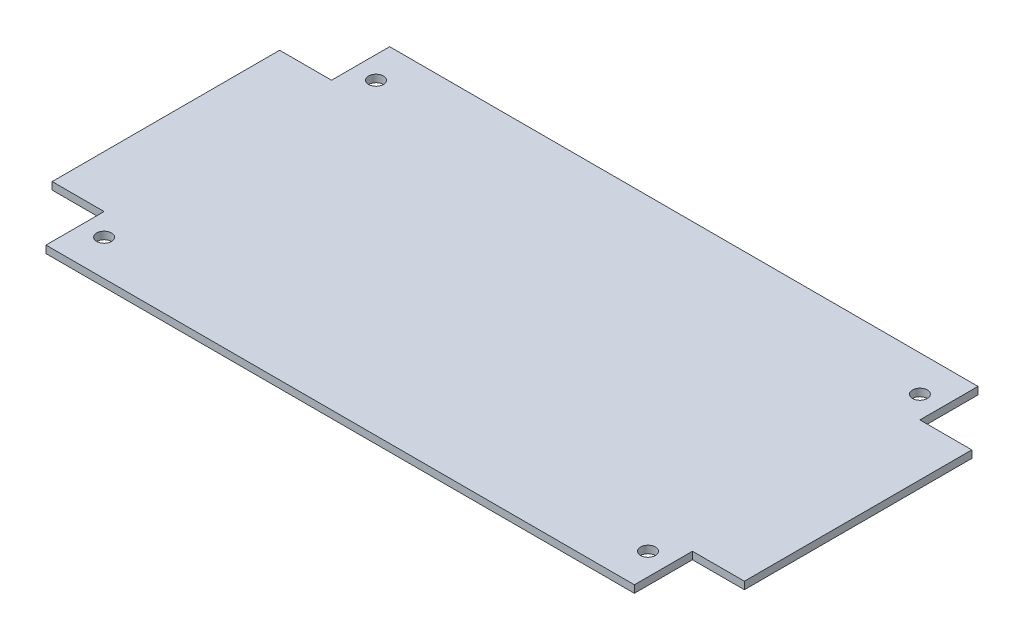
SolidWorks part; units mm, degrees
ref_plane "Спереди" through (0, 0, 0) normal (0, 0, 1) x (1, 0, 0)
ref_plane "Сверху" through (0, 0, 0) normal (0, 1, 0) x (1, 0, 0)
ref_plane "Справа" through (0, 0, 0) normal (1, 0, 0) x (0, 0, -1)
sketch "Эскиз1" plane through (0, 0, 0) normal (0, 1, 0) x (1, 0, 0)
  line L0 (-59.5, 34.75) -> (59.5, 34.75)
  line L1 (59.5, 34.75) -> (59.5, 23)
  line L2 (59.5, 23) -> (70, 23)
  line L3 (70, 23) -> (70, -23)
  line L4 (70, -23) -> (59.5, -23)
  line L5 (59.5, -23) -> (59.5, -34.75)
  line L6 (59.5, -34.75) -> (-59.5, -34.75)
  line L7 (-59.5, -34.75) -> (-59.5, -23)
  line L8 (-59.5, -23) -> (-70, -23)
  line L9 (-70, -23) -> (-70, 23)
  line L10 (-70, 23) -> (-59.5, 23)
  line L11 (-59.5, 23) -> (-59.5, 34.75)
  line L12 (-70, 0) -> (70, 0) construction
  line L13 (0, 34.75) -> (0, -34.75) construction
  point P16 (0, 0)
  point P17 (0, 0)
  dimension "D1" = 69.5
  dimension "D2" = 119
  dimension "D3" = 46
  dimension "D4" = 140
extrude "Бобышка-Вытянуть1" add sketch "Эскиз1" along normal blind 1.5
sketch "Эскиз2" plane through (0, 0, 0) normal (0, 1, 0) x (1, 0, 0)
  line L1 (-55, 27.5) -> (55, 27.5) construction
  line L2 (-55, 27.5) -> (-55, -27.5) construction
  line L3 (-55, -27.5) -> (55, -27.5) construction
  line L4 (55, 27.5) -> (55, -27.5) construction
  line L5 (-55, 27.5) -> (55, -27.5) construction
  line L6 (-55, -27.5) -> (55, 27.5) construction
  circle A0 centre (-55, 27.5) radius 1.5
  circle A1 centre (-55, -27.5) radius 1.5
  circle A2 centre (55, -27.5) radius 1.5
  circle A3 centre (55, 27.5) radius 1.5
  point P0 (0, 0)
  dimension "D3" = 3
  dimension "D1" = 110
  dimension "D2" = 55
extrude "Вырез-Вытянуть2" cut sketch "Эскиз2" along normal blind 1.5
